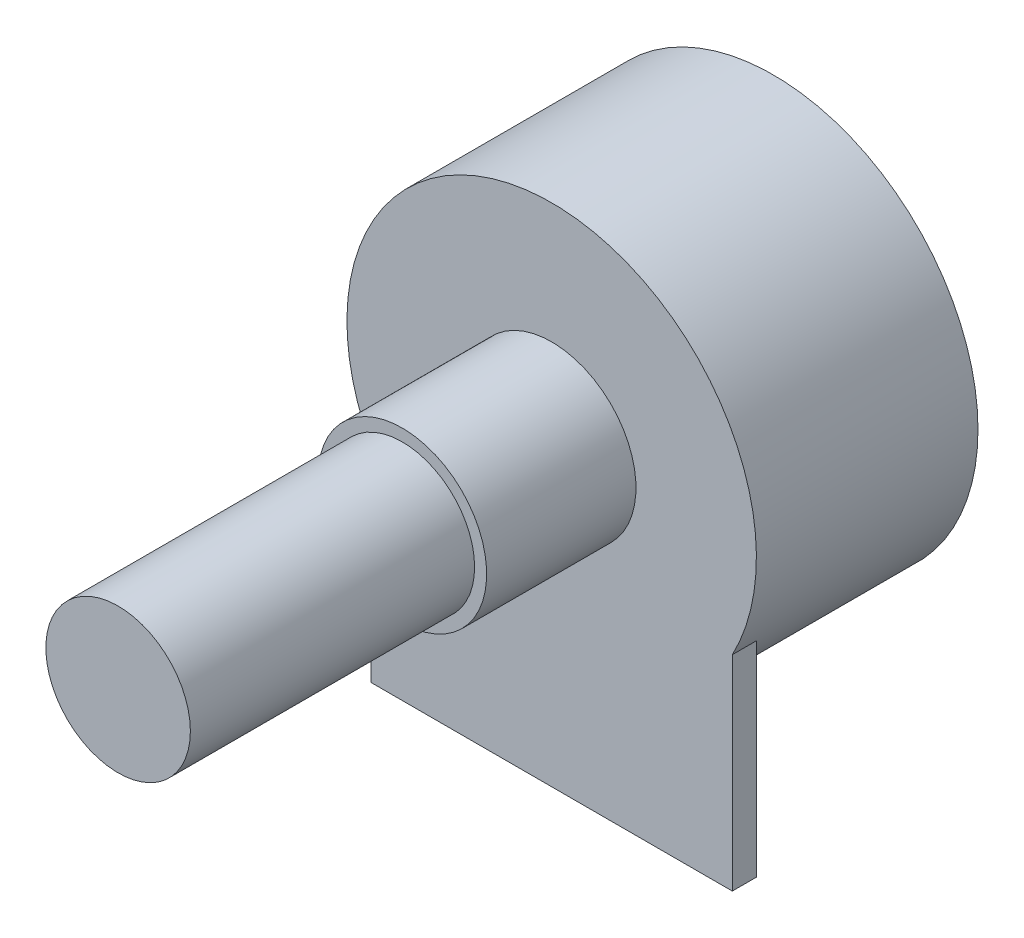
SolidWorks part; units mm, degrees
ref_plane "Piano frontale" through (0, 0, 0) normal (0, 0, 1) x (1, 0, 0)
ref_plane "Piano superiore" through (0, 0, 0) normal (0, 1, 0) x (1, 0, 0)
ref_plane "Piano destro" through (0, 0, 0) normal (1, 0, 0) x (0, 0, -1)
sketch "Schizzo1" plane through (0, 0, 0) normal (0, 0, 1) x (1, 0, 0)
  circle A0 centre (0, 0) radius 8.5
  point P7 (7.5, -4)
  dimension "D1" = 17
extrude "Estrusione-Estrusione1" add sketch "Schizzo1" along normal blind 9.2
sketch "Schizzo2" plane through (0, 0, 9.2) normal (0, 0, 1) x (1, 0, 0)
  line L1 (-7.5, -4) -> (7.5, -4)
  line L2 (-7.5, -4) -> (-7.5, -12.5)
  line L3 (-7.5, -12.5) -> (7.5, -12.5)
  line L4 (7.5, -4) -> (7.5, -12.5)
  circle A0 centre (0, 0) radius 8.5 construction
  dimension "D1" = 12.5
  dimension "D2" = 15
  dimension "D3" = 7.5
extrude "Estrusione-Estrusione2" add sketch "Schizzo2" against normal blind 1
sketch "Schizzo3" plane through (0, 0, 9.2) normal (0, 0, 1) x (1, 0, 0)
  circle A0 centre (0, 0) radius 3.5
  dimension "D1" = 7
extrude "Estrusione-Estrusione3" add sketch "Schizzo3" along normal blind 6.2
sketch "Schizzo4" plane through (0, 0, 15.4) normal (0, 0, 1) x (1, 0, 0)
  circle A0 centre (0, 0) radius 3
  dimension "D1" = 6
extrude "Estrusione-Estrusione4" add sketch "Schizzo4" along normal blind 11.8
